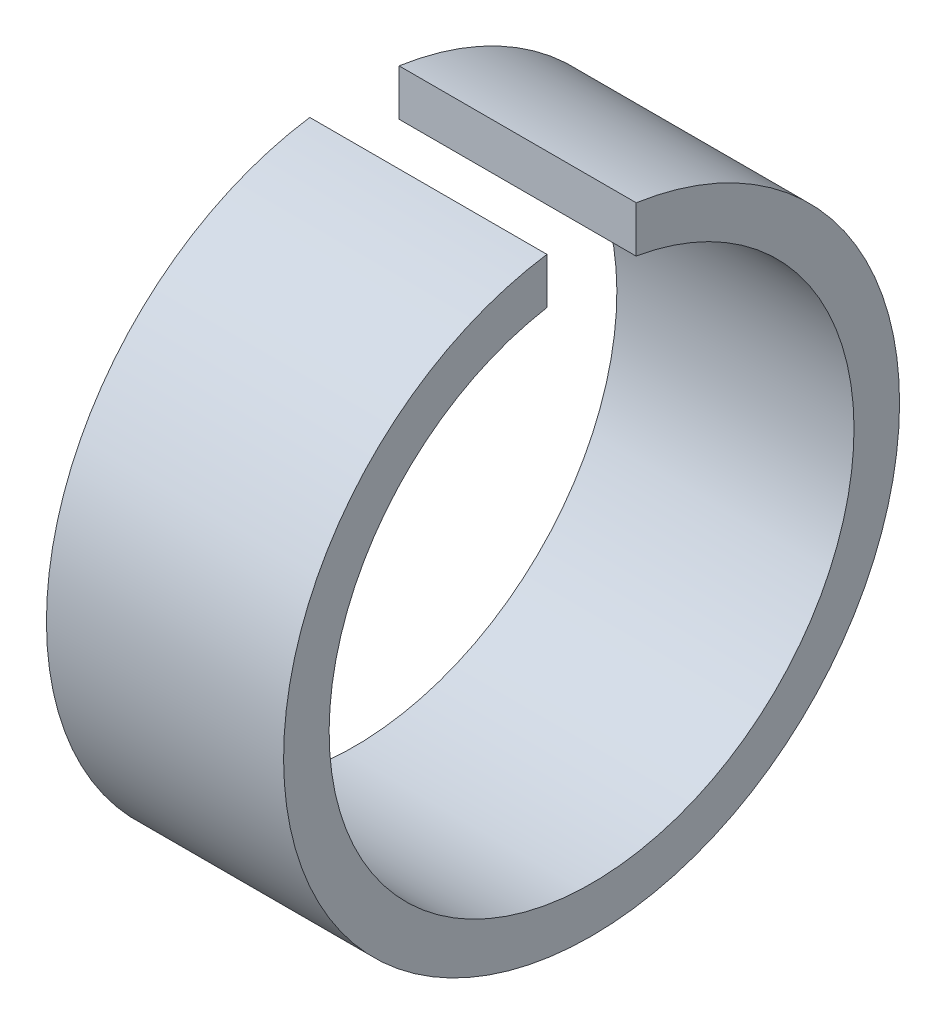
SolidWorks part; units mm, degrees
ref_plane "Front Plane" through (0, 0, 0) normal (0, 0, 1) x (1, 0, 0)
ref_plane "Top Plane" through (0, 0, 0) normal (0, 1, 0) x (1, 0, 0)
ref_plane "Right Plane" through (0, 0, 0) normal (1, 0, 0) x (0, 0, -1)
sketch "Sketch1" plane through (0, 0, 0) normal (1, 0, 0) x (0, 0, -1)
  line L0 (3.5711, 20.7773) -> (3.5872, 24.4781)
  line L1 (-3.5711, 20.7773) -> (-3.5872, 24.4781)
  arc A0 (-3.5872, 24.4781) -> (3.5872, 24.4781) centre (0, 0) ccw
  arc A1 (-3.5711, 20.7773) -> (3.5711, 20.7773) centre (0, 0) ccw
  dimension "D1" = 21.082
  dimension "D2" = 3.6576
extrude "Boss-Extrude1" add sketch "Sketch1" along normal blind 19.05
